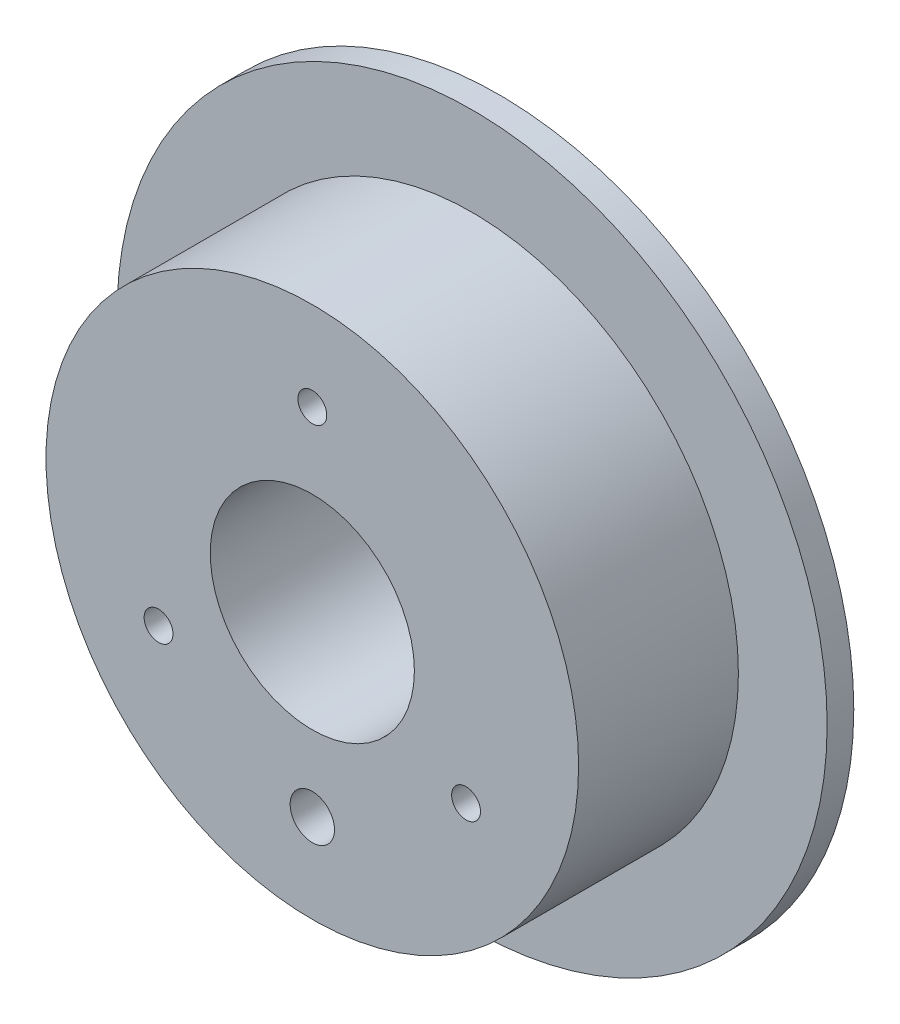
SolidWorks part; units mm, degrees
ref_plane "Front Plane" through (0, 0, 0) normal (0, 0, 1) x (1, 0, 0)
ref_plane "Top Plane" through (0, 0, 0) normal (0, 1, 0) x (1, 0, 0)
ref_plane "Right Plane" through (0, 0, 0) normal (1, 0, 0) x (0, 0, -1)
sketch "Sketch1" plane through (0, 0, 0) normal (0, 0, 1) x (1, 0, 0)
  circle A0 centre (0, 0) radius 40
  dimension "D1" = 80
extrude "Boss-Extrude1" add sketch "Sketch1" along normal blind 3
sketch "Sketch2" plane through (0, 0, 3) normal (0, 0, 1) x (1, 0, 0)
  circle A0 centre (0, 0) radius 30
  dimension "D1" = 60
extrude "Boss-Extrude2" add sketch "Sketch2" along normal blind 18
sketch "Sketch3" plane through (0, 0, 21) normal (0, 0, 1) x (1, 0, 0)
  circle A0 centre (0, 20) radius 1.625
  circle A1 centre (17.3205, -10) radius 1.625
  circle A2 centre (-17.3205, -10) radius 1.625
  circle A3 centre (0, 0) radius 11.5
  circle A4 centre (0, -20) radius 2.5
  point P9 (0, 0)
  dimension "D2" = 3.25
  dimension "D4" = 23
  dimension "D6" = 5
  dimension "D1" = 20
  dimension "D5" = 20
  dimension "D3" = 3
extrude "Cut-Extrude1" cut sketch "Sketch3" against normal through all
